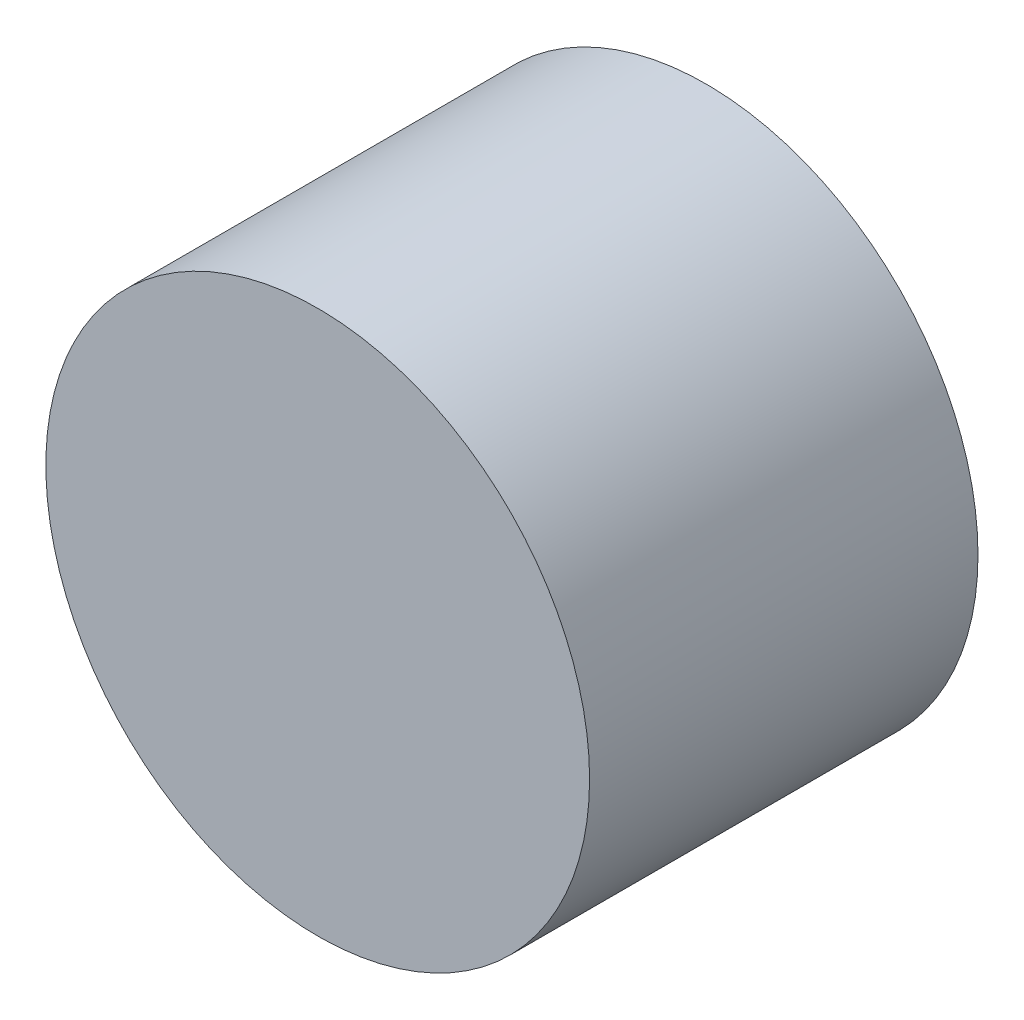
SolidWorks part; units mm, degrees
ref_plane "Ebene vorne" through (0, 0, 0) normal (0, 0, 1) x (1, 0, 0)
ref_plane "Ebene oben" through (0, 0, 0) normal (0, 1, 0) x (1, 0, 0)
ref_plane "Ebene rechts" through (0, 0, 0) normal (1, 0, 0) x (0, 0, -1)
sketch "Skizze1" plane through (0, 0, 0) normal (0, 0, 1) x (1, 0, 0)
  circle A0 centre (0, 0) radius 3.5
  dimension "D1" = 7
extrude "Aufsatz-Linear austragen1" add sketch "Skizze1" along normal blind 5
